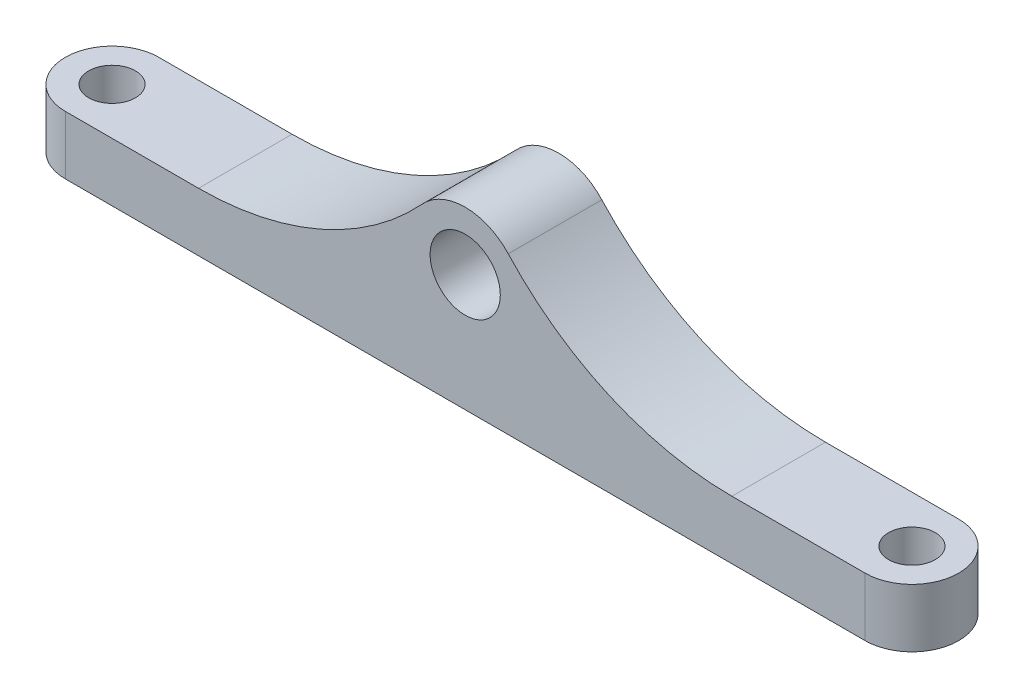
SolidWorks part; units mm, degrees
ref_plane "Front Plane" through (0, 0, 0) normal (0, 0, 1) x (1, 0, 0)
ref_plane "Top Plane" through (0, 0, 0) normal (0, 1, 0) x (1, 0, 0)
ref_plane "Right Plane" through (0, 0, 0) normal (1, 0, 0) x (0, 0, -1)
sketch "Sketch1" plane through (0, 0, 0) normal (0, 1, 0) x (1, 0, 0)
  line L0 (0, 0) -> (34.19, 0)
  line L1 (0, 0) -> (-34.19, 0)
  line L3 (-22.7989, -4) -> (22.7989, -4)
  line L5 (-22.7989, 4) -> (22.7989, 4)
  line L6 (-22.7989, -4) -> (-22.7989, 4)
  line L7 (22.7989, -4) -> (22.7989, 4)
  line L8 (-22.7989, 0) -> (22.7989, 0)
  line L9 (-34.19, -4) -> (34.19, -4)
  line L10 (-34.19, 4) -> (34.19, 4)
  circle A0 centre (-34.19, 0) radius 2
  circle A1 centre (34.19, 0) radius 2
  circle A2 centre (-34.19, 0) radius 4
  circle A3 centre (34.19, 0) radius 4
  circle A8 centre (0, 0) radius 3
  dimension "D1" = 4
  dimension "D3" = 2
  dimension "D6" = 6
  dimension "D2" = 68.38
extrude "Boss-Extrude1" add sketch "Sketch1" along normal blind 5
sketch "Sketch2" plane through (0, 0, 4) normal (0, 0, 1) x (1, 0, 0)
  line L0 (-34.19, 5) -> (34.19, 5) construction
  line L1 (-22.7989, 5) -> (22.7989, 5)
  line L3 (0, 10) -> (0, 0)
  line L4 (22.7989, 5) -> (22.7989, 0) construction
  circle A0 centre (0, 10) radius 3
  circle A1 centre (0, 10) radius 5
  arc A2 (-22.7989, 5) -> (-3.6785, 13.3865) centre (-22.7989, 30.9895) ccw
  arc A3 (22.7989, 5) -> (3.6785, 13.3865) centre (22.7989, 30.9895) cw
  point P7 (0, 5)
  dimension "D1" = 6
  dimension "D2" = 2
extrude "Boss-Extrude2" add sketch "Sketch2" against normal up to surface (8 mm away)
